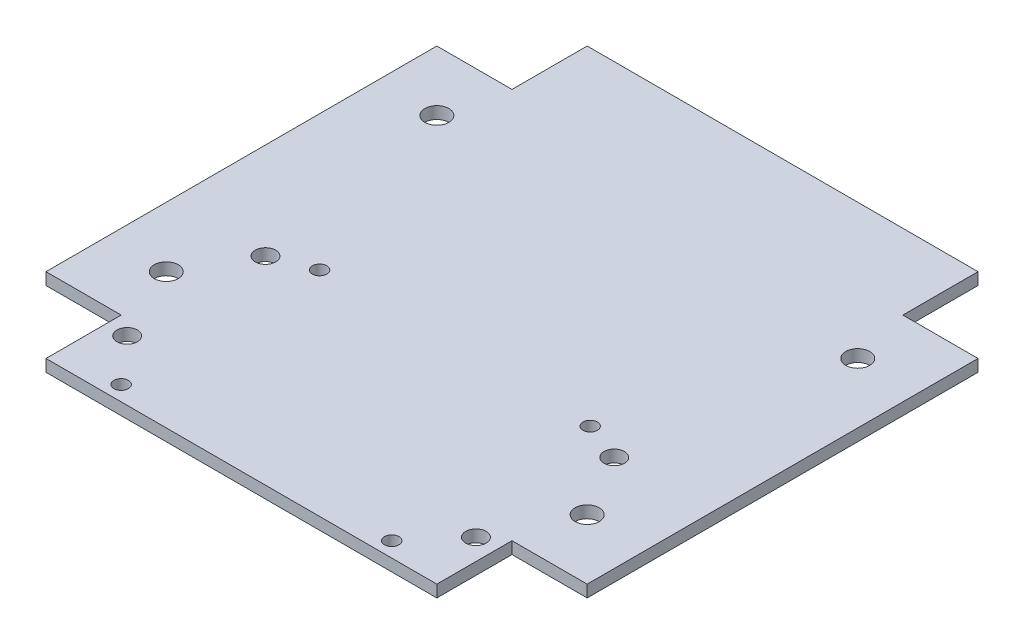
SolidWorks part; units mm, degrees
ref_plane "Front Plane" through (0, 0, 0) normal (0, 0, 1) x (1, 0, 0)
ref_plane "Top Plane" through (0, 0, 0) normal (0, 1, 0) x (1, 0, 0)
ref_plane "Right Plane" through (0, 0, 0) normal (1, 0, 0) x (0, 0, -1)
sketch "Sketch1" plane through (0, 0, 0) normal (0, 1, 0) x (1, 0, 0)
  line L0 (-53.9706, 35.1103) -> (-41.4706, 35.1103)
  line L1 (-41.4706, 35.1103) -> (-41.4706, 47.6103)
  line L2 (-41.4706, 47.6103) -> (23.5294, 47.6103)
  line L3 (23.5294, 47.6103) -> (23.5294, 35.1103)
  line L4 (23.5294, 35.1103) -> (36.0294, 35.1103)
  line L5 (36.0294, 35.1103) -> (36.0294, -29.8897)
  line L6 (36.0294, -29.8897) -> (23.5294, -29.8897)
  line L7 (23.5294, -29.8897) -> (23.5294, -42.3897)
  line L8 (23.5294, -42.3897) -> (-41.4706, -42.3897)
  line L9 (-41.4706, -42.3897) -> (-41.4706, -29.8897)
  line L10 (-41.4706, -29.8897) -> (-53.9706, -29.8897)
  line L11 (-53.9706, -29.8897) -> (-53.9706, 35.1103)
  dimension "D1" = 90
  dimension "D2" = 90
  dimension "D3" = 12.5
  dimension "D4" = 12.5
  dimension "D5" = 12.5
  dimension "D6" = 12.5
  dimension "D7" = 12.5
  dimension "D8" = 12.5
  dimension "D9" = 12.5
  dimension "D10" = 12.5
extrude "Boss-Extrude1" add sketch "Sketch1" along normal blind 2
sketch "Sketch2" plane through (0, 2, 0) normal (0, 1, 0) x (1, 0, 0)
  line L0 (-53.9706, 25.1103) -> (36.0294, 25.1103) construction
  line L1 (-53.9706, 35.1103) -> (-53.9706, -29.8897) construction
  line L2 (36.0294, -29.8897) -> (36.0294, 35.1103) construction
  line L3 (-53.9706, -19.8897) -> (36.0294, -19.8897) construction
  line L4 (-43.9706, 47.6103) -> (-43.9706, -42.3897) construction
  line L5 (23.5294, 47.6103) -> (-41.4706, 47.6103) construction
  line L6 (-41.4706, -42.3897) -> (23.5294, -42.3897) construction
  line L7 (26.0294, 47.6103) -> (26.0294, -42.3897) construction
  line L11 (-31.4706, -39.8897) -> (13.5294, -39.8897)
  line L12 (-31.4706, -39.8897) -> (-31.4706, -6.8897)
  line L13 (-31.4706, -6.8897) -> (13.5294, -6.8897)
  line L14 (13.5294, -39.8897) -> (13.5294, -6.8897)
  point P16 (-43.9706, 25.1103)
  point P17 (-43.9706, -19.8897)
  point P18 (26.0294, -19.8897)
  point P19 (26.0294, 25.1103)
  point P33 (-31.4706, -39.8897)
  point P34 (13.5294, -39.8897)
  dimension "D1" = 45
  dimension "D2" = 22.5
  dimension "D3" = 10
  dimension "D4" = 70
  dimension "D5" = 45
  dimension "D6" = 22.5
  dimension "D7" = 33
  dimension "D8" = 2.5
hole_wizard "Ø4.0mm Dowel Hole1" positions "Sketch5" profile "Sketch6" hole size "Ø4.0" standard "ISO" end condition through all
sketch "Sketch5" plane through (0, 2, 0) normal (0, 1, 0) x (1, 0, 0)
  point P0 (-43.9706, 25.1103)
  point P3 (26.0294, 25.1103)
  point P6 (-43.9706, -19.8897)
  point P9 (26.0294, -19.8897)
sketch "Sketch6" plane through (-43.9706, 2, -25.1103) normal (1, 0, 0) x (0, 0, 1)
  line L0 (0, 0) -> (0, 2)
  line L1 (0, 2) -> (2, 2)
  line L2 (2, 2) -> (2, 0)
  line L5 (2, 0) -> (0, 0)
  line L11 (0, -6.35) -> (0, 107.95) construction
  dimension "Thru Hole Dia." = 4
  dimension "Thru Hole Depth" = 2
sketch "Sketch11" plane through (0, 2, 0) normal (0, 1, 0) x (1, 0, 0)
  line L0 (-41.4706, -42.3897) -> (23.5294, -42.3897) construction
  line L1 (-37.9706, -9.3897) -> (20.0294, -9.3897)
  line L2 (-37.9706, -9.3897) -> (-37.9706, -32.3897)
  line L3 (-37.9706, -32.3897) -> (20.0294, -32.3897)
  line L4 (20.0294, -9.3897) -> (20.0294, -32.3897)
  line L5 (-8.9706, -9.3897) -> (-8.9706, -32.3897) construction
  line L6 (-53.9706, 35.1103) -> (-53.9706, -29.8897) construction
  dimension "D1" = 58
  dimension "D2" = 23
  dimension "D3" = 10
  dimension "D4" = 45
hole_wizard "M3 Clearance Hole1" positions "Sketch12" profile "Sketch13" hole size "M3" standard "ISO"
sketch "Sketch12" plane through (0, 2, 0) normal (0, 1, 0) x (1, 0, 0)
  point P0 (-37.9706, -9.3897)
  point P3 (-37.9706, -32.3897)
  point P6 (20.0294, -32.3897)
  point P9 (20.0294, -9.3897)
sketch "Sketch13" plane through (-37.9706, 2, 9.3897) normal (1, 0, 0) x (0, 0, 1)
  line L0 (0, 0) -> (0, 11.0215)
  line L1 (0, 11.0215) -> (1.7, 10)
  line L2 (1.7, 10) -> (1.7, 0)
  line L5 (1.7, 0) -> (0, 0)
  line L10 (0, 11.0215) -> (-1.7, 10) construction
  line L11 (0, -6.35) -> (0, 107.95) construction
  dimension "Hole Dia." = 3.4
  dimension "Hole Depth" = 10
  dimension "Drill Angle" = 118
hole_wizard "M2 Clearance Hole1" positions "Sketch14" profile "Sketch15" hole size "M2" standard "ISO"
sketch "Sketch14" plane through (0, 2, 0) normal (0, 1, 0) x (1, 0, 0)
  point P0 (-31.4706, -39.8897)
  point P3 (-31.4706, -6.8897)
  point P6 (13.5294, -39.8897)
  point P9 (13.5294, -6.8897)
sketch "Sketch15" plane through (-31.4706, 2, 39.8897) normal (1, 0, 0) x (0, 0, 1)
  line L0 (0, 0) -> (0, 10.721)
  line L1 (0, 10.721) -> (1.2, 10)
  line L2 (1.2, 10) -> (1.2, 0)
  line L5 (1.2, 0) -> (0, 0)
  line L10 (0, 10.721) -> (-1.2, 10) construction
  line L11 (0, -6.35) -> (0, 107.95) construction
  dimension "Hole Dia." = 2.4
  dimension "Hole Depth" = 10
  dimension "Drill Angle" = 118
